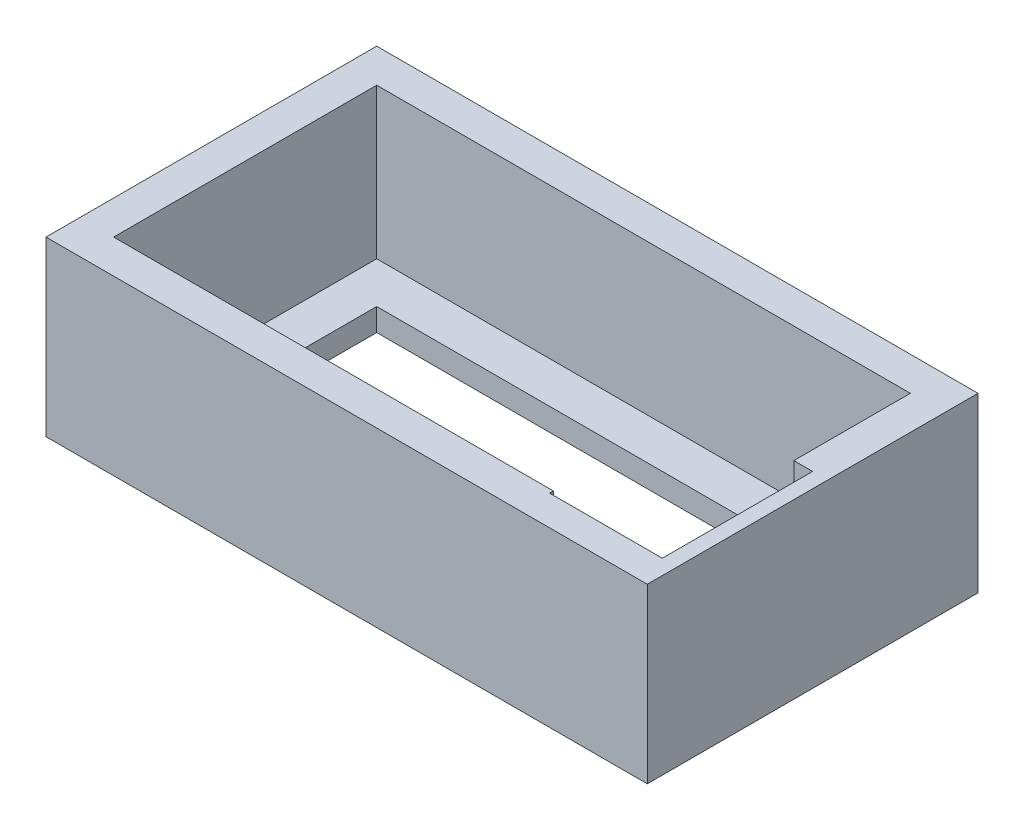
SolidWorks part; units mm, degrees
ref_plane "Front Plane" through (0, 0, 0) normal (0, 0, 1) x (1, 0, 0)
ref_plane "Top Plane" through (0, 0, 0) normal (0, 1, 0) x (1, 0, 0)
ref_plane "Right Plane" through (0, 0, 0) normal (1, 0, 0) x (0, 0, -1)
sketch "Sketch1" plane through (0, 0, 0) normal (0, 1, 0) x (1, 0, 0)
  line L0 (-30, -12) -> (30, -12)
  line L1 (-40, -22) -> (40, -22)
  line L2 (-40, -22) -> (-40, 22)
  line L3 (-40, 22) -> (40, 22)
  line L4 (40, -22) -> (40, 22)
  line L5 (-40, -22) -> (40, 22) construction
  line L6 (-40, 22) -> (40, -22) construction
  line L7 (30, -12) -> (30, 12)
  line L8 (-30, 12) -> (30, 12)
  line L9 (-30, -12) -> (-30, 12)
  point P0 (0, 0)
  dimension "D1" = 80
  dimension "D2" = 44
  dimension "D3" = 10
extrude "Boss-Extrude1" add sketch "Sketch1" along normal blind 3
sketch "Sketch2" plane through (0, 3, 0) normal (0, 1, 0) x (1, 0, 0)
  line L0 (-40, 22) -> (-40, -22)
  line L1 (-40, -22) -> (40, -22)
  line L2 (40, -22) -> (40, 22)
  line L3 (40, 22) -> (-40, 22)
  line L4 (35.5, 17.5) -> (-35.5, 17.5)
  line L5 (-35.5, 17.5) -> (-35.5, -17.5)
  line L6 (-35.5, -17.5) -> (35.5, -17.5)
  line L7 (35.5, -17.5) -> (35.5, 17.5)
  dimension "D1" = 35
extrude "Boss-Extrude2" add sketch "Sketch2" along normal blind 20
sketch "Sketch3" plane through (0, 0, 0) normal (0, -1, 0) x (-1, 0, 0)
  line L0 (40, -22) -> (-40, -22) construction
  line L1 (-38, -18) -> (-23, -18)
  line L2 (-38, -18) -> (-38, 2)
  line L3 (-38, 2) -> (-23, 2)
  line L4 (-23, -18) -> (-23, 2)
  line L5 (-40, -22) -> (-40, 22) construction
  dimension "D1" = 4
  dimension "D2" = 2
  dimension "D3" = 20
  dimension "D4" = 15
extrude "Cut-Extrude1" cut sketch "Sketch3" against normal up to next
